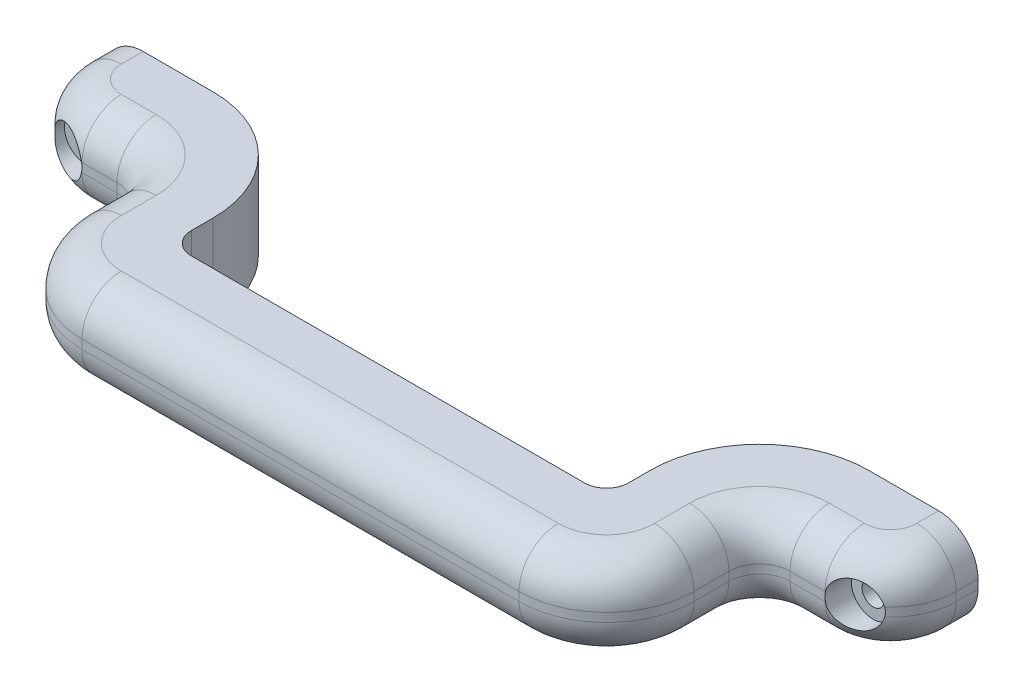
SolidWorks part; units mm, degrees
ref_plane "Спереди" through (0, 0, 0) normal (0, 0, 1) x (1, 0, 0)
ref_plane "Сверху" through (0, 0, 0) normal (0, 1, 0) x (1, 0, 0)
ref_plane "Справа" through (0, 0, 0) normal (1, 0, 0) x (0, 0, -1)
sketch "Эскиз1" plane through (0, 0, 0) normal (0, 1, 0) x (1, 0, 0)
  line L0 (-78.6136, 20) -> (-53.6136, 20)
  line L1 (-28.6136, -5) -> (-28.6136, -10)
  line L2 (-23.6136, -15) -> (66.3864, -15)
  line L3 (71.3864, -10) -> (71.3864, -5)
  line L4 (96.3864, 20) -> (121.3864, 20)
  line L5 (121.3864, 20) -> (121.3864, 15)
  line L6 (106.3864, 0) -> (98.3864, 0)
  line L7 (91.3864, -7) -> (91.3864, -15)
  line L8 (71.3864, -35) -> (-28.6136, -35)
  line L9 (-48.6136, -15) -> (-48.6136, -7)
  line L10 (-55.6136, 0) -> (-63.6136, 0)
  line L11 (-78.6136, 15) -> (-78.6136, 20)
  arc A0 (71.3864, -5) -> (96.3864, 20) centre (96.3864, -5) cw
  arc A1 (-53.6136, 20) -> (-28.6136, -5) centre (-53.6136, -5) cw
  arc A2 (98.3864, 0) -> (91.3864, -7) centre (98.3864, -7) ccw
  arc A3 (-48.6136, -7) -> (-55.6136, 0) centre (-55.6136, -7) ccw
  arc A4 (91.3864, -15) -> (71.3864, -35) centre (71.3864, -15) cw
  arc A5 (-28.6136, -35) -> (-48.6136, -15) centre (-28.6136, -15) cw
  arc A6 (121.3864, 15) -> (106.3864, 0) centre (106.3864, 15) cw
  arc A7 (-63.6136, 0) -> (-78.6136, 15) centre (-63.6136, 15) cw
  arc A8 (66.3864, -15) -> (71.3864, -10) centre (66.3864, -10) ccw
  arc A9 (-28.6136, -10) -> (-23.6136, -15) centre (-23.6136, -10) ccw
  point P15 (71.3864, 20)
  point P18 (-28.6136, 20)
  point P33 (71.3864, -15)
  point P36 (-28.6136, -15)
  dimension "D11" = 25
  dimension "D12" = 7
  dimension "D13" = 20
  dimension "D14" = 15
  dimension "D15" = 5
  dimension "D1" = 100
  dimension "D2" = 20
  dimension "D3" = 20
  dimension "D4" = 20
  dimension "D5" = 20
  dimension "D6" = 20
  dimension "D7" = 35
  dimension "D8" = 35
  dimension "D9" = 50
  dimension "D10" = 50
extrude "Бобышка-Вытянуть1" add sketch "Эскиз1" along normal blind 20
fillet "Скругление1" radius 9 26 edges at (-78.6136, 0, -17.5) (121.3864, 0, -17.5) (116.993, 0, -4.3934) (102.3864, 0, 0) (93.4367, 0, 2.0503) (91.3864, 0, 11) (85.5286, 0, 29.1421) (21.3864, 0, 35) (-42.7557, 0, 29.1421) (-48.6136, 0, 11) (-50.6638, 0, 2.0503) (-59.6136, 0, 0) (-78.6136, 20, -17.5) (121.3864, 20, -17.5) (116.993, 20, -4.3934) (102.3864, 20, 0) (93.4367, 20, 2.0503) (91.3864, 20, 11) (85.5286, 20, 29.1421) (21.3864, 20, 35) (-42.7557, 20, 29.1421) (-48.6136, 20, 11) (-50.6638, 20, 2.0503) (-59.6136, 20, 0) (-74.2202, 0, -4.3934) (-74.2202, 20, -4.3934)
sketch "Эскиз2" plane through (0, 0, -20) normal (0, 0, -1) x (-1, 0, 0)
  line L0 (-124.613, 10) -> (81.2731, 10) construction
  line L1 (-121.3864, 11) -> (-121.3864, 9) construction
  line L2 (78.6136, 11) -> (78.6136, 9) construction
  circle A0 centre (-111.3864, 10) radius 2.55
  circle A2 centre (68.6136, 10) radius 2.55
  dimension "D1" = 5.1
  dimension "D2" = 10
  dimension "D3" = 5.1
  dimension "D4" = 10
extrude "Вырез-Вытянуть1" cut sketch "Эскиз2" against normal through all
sketch "Эскиз3" plane through (0, 0, 0) normal (0, 0, 1) x (1, 0, 0)
  circle A0 centre (-68.6136, 10) radius 5
  circle A1 centre (111.3864, 10) radius 5
  dimension "D1" = 10
extrude "Вырез-Вытянуть2" cut sketch "Эскиз3" against normal blind 6
